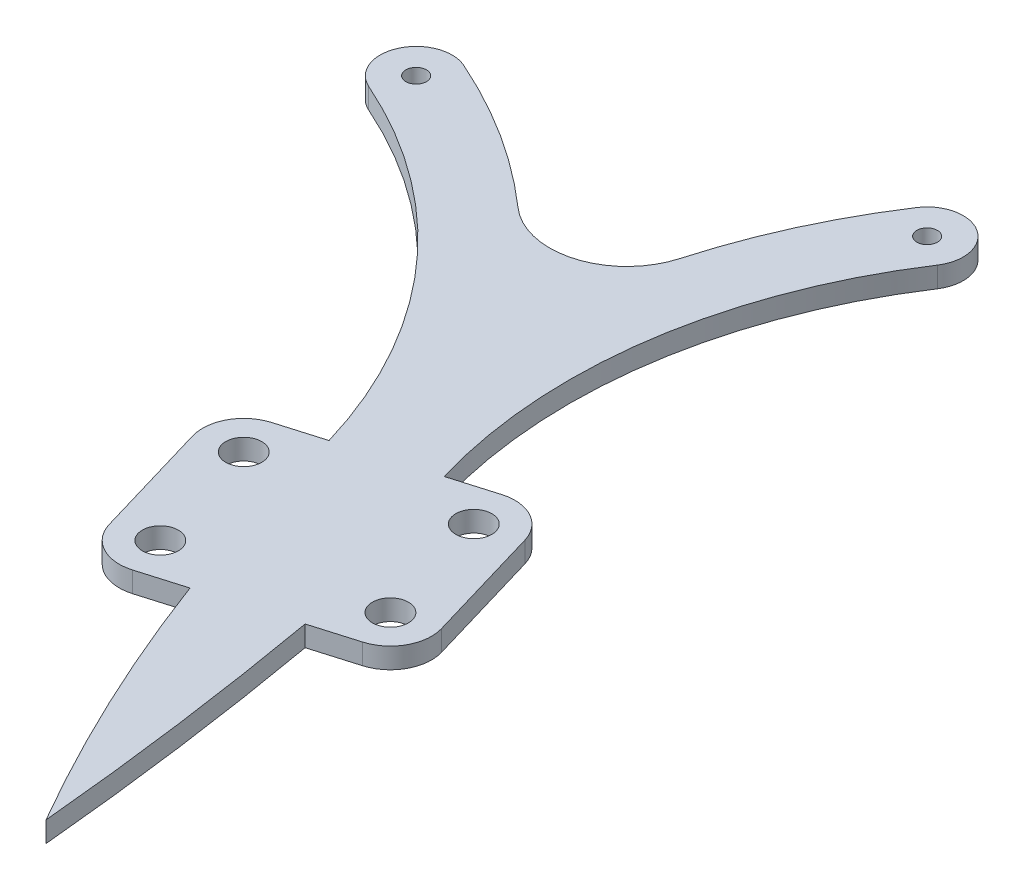
SolidWorks part; units mm, degrees
ref_plane "Plan de face" through (0, 0, 0) normal (0, 0, 1) x (1, 0, 0)
ref_plane "Plan de dessus" through (0, 0, 0) normal (0, 1, 0) x (1, 0, 0)
ref_plane "Plan de droite" through (0, 0, 0) normal (1, 0, 0) x (0, 0, -1)
sketch "Esquisse1" plane through (-102.8474, 0, 18.1348) normal (0, -1, 0) x (-0.9359, 0, 0.3523)
  line L0 (-17.1331, -55.155) -> (-22.8819, 23.516) construction
  line L1 (-29.6811, -6.9299) -> (-25.1931, -6.602)
  line L2 (-11.7273, -5.6407) -> (-16.2153, -5.9687)
  line L3 (-28.515, -22.8874) -> (-11.4358, -9.6301) construction
  line L7 (-32.5044, -23.1789) -> (-33.379, -11.2108)
  line L9 (-23.7355, -26.5488) -> (-28.2235, -26.8767)
  line L11 (-7.4464, -9.3386) -> (-6.5719, -21.3067)
  line L12 (-10.2697, -25.5875) -> (-14.7578, -25.9155)
  line L14 (-48.915, 32.7739) -> (-4.6124, 36.0113) construction
  line L15 (-22.8819, 23.516) -> (-23.9483, 38.1089) construction
  line L16 (-23.7355, -26.5488) -> (-25.1931, -6.602) construction
  line L17 (-16.2153, -5.9687) -> (-14.7578, -25.9155) construction
  arc A1 (-23.7355, -26.5488) -> (-17.1331, -55.155) centre (320.3001, 37.7903) ccw
  arc A2 (-41.5781, 35.9876) -> (-45.7018, 30.3312) centre (-43.6399, 33.1594) ccw
  arc A3 (-1.2941, 33.5772) -> (-6.1985, 38.5719) centre (-3.7463, 36.0746) ccw
  arc A4 (-17.1331, -55.155) -> (-14.7578, -25.9155) centre (-189.757, -26.4153) ccw
  arc A6 (-29.6811, -6.9299) -> (-33.379, -11.2108) centre (-29.3896, -10.9193) ccw
  arc A7 (-32.5044, -23.1789) -> (-28.2235, -26.8767) centre (-28.515, -22.8874) ccw
  arc A8 (-25.1931, -6.602) -> (-45.7018, 30.3312) centre (-75.2963, -10.2632) ccw
  circle A9 centre (-43.6399, 33.1594) radius 1
  arc A10 (-7.4464, -9.3386) -> (-11.7273, -5.6407) centre (-11.4358, -9.6301) ccw
  arc A11 (-10.2697, -25.5875) -> (-6.5719, -21.3067) centre (-10.5612, -21.5982) ccw
  circle A16 centre (-29.3896, -10.9193) radius 1.75
  circle A17 centre (-28.515, -22.8874) radius 1.75
  circle A18 centre (-10.5612, -21.5982) radius 1.75
  circle A19 centre (-11.4358, -9.6301) radius 1.75
  circle A20 centre (-3.7463, 36.0746) radius 1
  arc A21 (-1.2941, 33.5772) -> (-16.2153, -5.9687) centre (33.9374, -2.304) ccw
  arc A22 (-29.2542, 23.7394) -> (-41.5781, 35.9876) centre (-75.2963, -10.2632) ccw
  arc A24 (-29.2542, 23.7394) -> (-16.6041, 24.6642) centre (-23.2211, 28.1949) ccw
  arc A25 (-6.1985, 38.5719) -> (-16.6041, 24.6642) centre (33.9374, -2.304) ccw
  point P24 (-19.9754, -16.2587)
  dimension "D3" = 20
  dimension "D4" = 7
  dimension "D5" = 7
  dimension "D6" = 2
  dimension "D7" = 2
  dimension "D8" = 7.5
  dimension "D9" = 3.5
  dimension "D10" = 3.5
  dimension "D11" = 3.5
  dimension "D12" = 3.5
  dimension "D15" = 2.25
  dimension "D16" = 2.25
  dimension "D17" = 2.25
  dimension "D18" = 2.25
  dimension "D19" = 45
  dimension "D21" = 9
  dimension "D24" = 18.0001
  dimension "D26" = 350
  dimension "D22" = 350
  dimension "D27" = 39
  dimension "D2" = 20
  dimension "D13" = 12
  dimension "D14" = 9
  dimension "D23" = 18
  dimension "D25" = 12
  dimension "D28" = 4.5
  dimension "D29" = 4.5
extrude "Boss.-Extru.1" add sketch "Esquisse1" along normal blind 2
